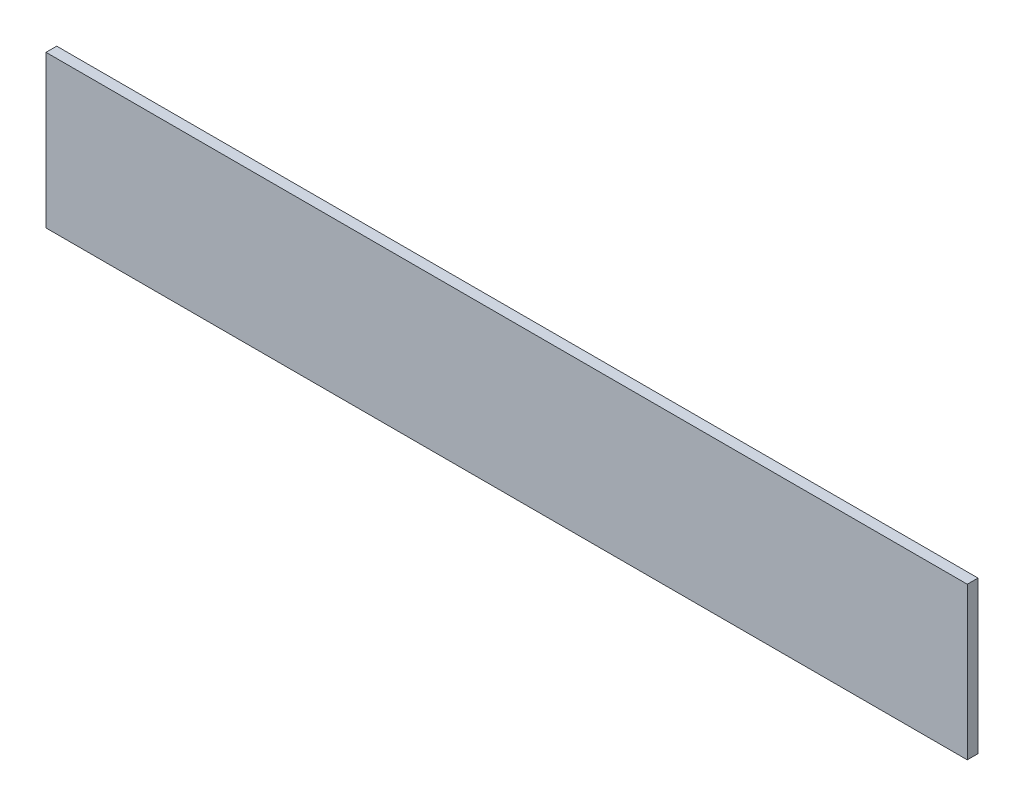
SolidWorks part; units mm, degrees
ref_plane "Alzado" through (0, 0, 0) normal (0, 0, 1) x (1, 0, 0)
ref_plane "Planta" through (0, 0, 0) normal (0, 1, 0) x (1, 0, 0)
ref_plane "Vista lateral" through (0, 0, 0) normal (1, 0, 0) x (0, 0, -1)
sketch "Croquis1" plane through (0, 0, 0) normal (0, 0, 1) x (1, 0, 0)
  line L1 (-74.1175, -24.3494) -> (355.8825, -24.3494)
  line L2 (-74.1175, -24.3494) -> (-74.1175, 46.6506)
  line L3 (-74.1175, 46.6506) -> (355.8825, 46.6506)
  line L4 (355.8825, -24.3494) -> (355.8825, 46.6506)
  dimension "D1" = 71
  dimension "D2" = 430
extrude "Saliente-Extruir1" add sketch "Croquis1" along normal blind 5
